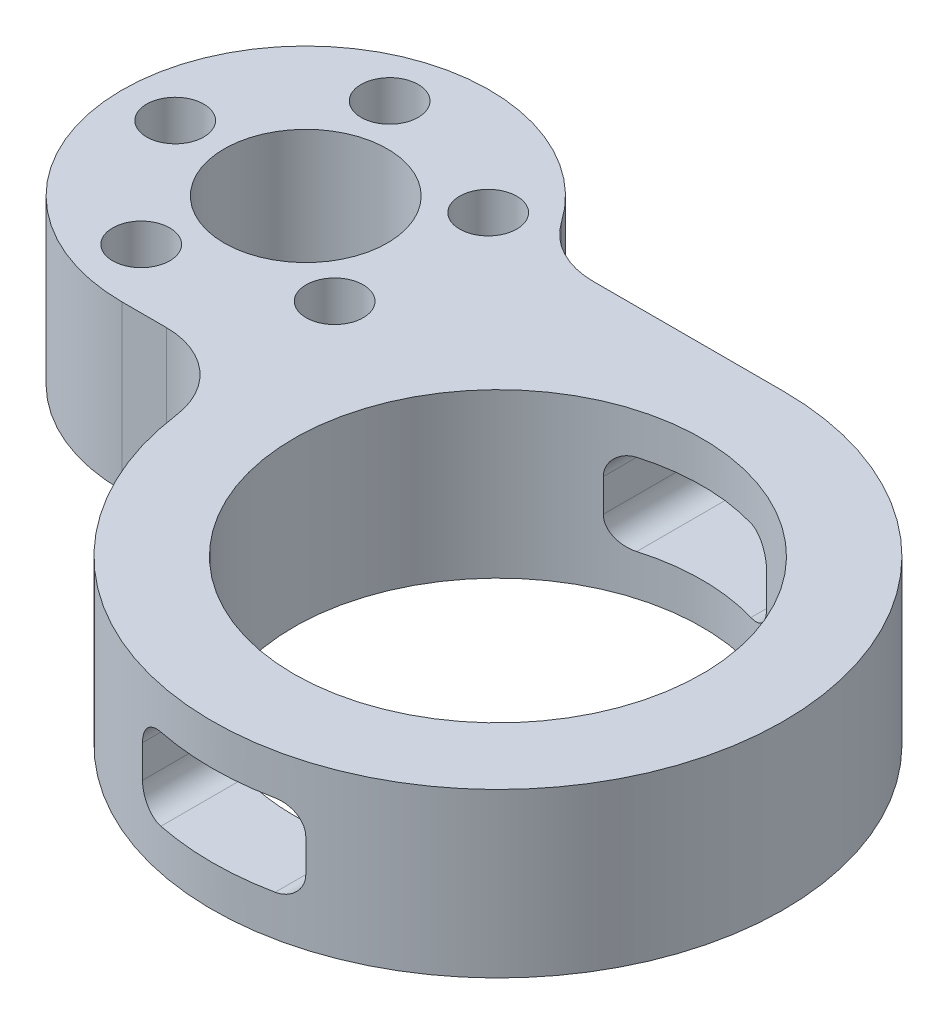
SolidWorks part; units mm, degrees
material "1060 Alloy"
ref_plane "Front Plane" through (0, 0, 0) normal (0, 0, 1) x (1, 0, 0)
ref_plane "Top Plane" through (0, 0, 0) normal (0, 1, 0) x (1, 0, 0)
ref_plane "Right Plane" through (0, 0, 0) normal (1, 0, 0) x (0, 0, -1)
sketch "Sketch1" plane through (0, 0, 0) normal (0, 1, 0) x (1, 0, 0)
  line L2 (-25, 1.9788) -> (-22.2962, 1.9788)
  line L3 (0, 17.5) -> (-11.6543, 17.5)
  circle A3 centre (0, 0) radius 12.5
  arc A4 (-17.3415, -2.3499) -> (0, 17.5) centre (0, 0) ccw
  circle A12 centre (-25, 13.2288) radius 5
  arc A13 (-15.7607, 19.6473) -> (-25, 1.9788) centre (-25, 13.2288) ccw
  arc A14 (-11.6543, 17.5) -> (-15.7607, 19.6473) centre (-11.6543, 22.5) cw
  arc A15 (-22.2962, 1.9788) -> (-17.3415, -2.3499) centre (-22.2962, -3.0212) cw
  circle A16 centre (-33, 13.2288) radius 1.75
  circle A17 centre (-27.4721, 20.8372) radius 1.75
  circle A18 centre (-18.5279, 17.931) radius 1.75
  circle A19 centre (-18.5279, 8.5265) radius 1.75
  circle A20 centre (-27.4721, 5.6203) radius 1.75
  point P14 (-40, 0)
  point P25 (-25, 13.2288)
  point P28 (-25, 13.2288)
  dimension "D2" = 17.5
  dimension "D3" = 25
  dimension "D4" = 25
  dimension "D5" = 10
  dimension "D8" = 5
  dimension "D9" = 3.5
  dimension "D10" = 8
  dimension "D6" = 22.5
  dimension "D7" = 5
  dimension "D13" = 5
  dimension "D11" = 20
  dimension "D12" = 40
extrude "Boss-Extrude1" add sketch "Sketch1" along normal blind 10
sketch "Sketch2" plane through (0, 0, 0) normal (0, 0, 1) x (1, 0, 0)
  line L1 (-3.5, 7.5) -> (3.5, 7.5)
  line L2 (-5, 6) -> (-5, 4)
  line L3 (-3.5, 2.5) -> (3.5, 2.5)
  line L4 (5, 6) -> (5, 4)
  line L5 (-5, 7.5) -> (5, 2.5) construction
  line L6 (-5, 2.5) -> (5, 7.5) construction
  arc A0 (3.5, 2.5) -> (5, 4) centre (3.5, 4) ccw
  arc A1 (-5, 4) -> (-3.5, 2.5) centre (-3.5, 4) ccw
  arc A2 (3.5, 7.5) -> (5, 6) centre (3.5, 6) cw
  arc A3 (-3.5, 7.5) -> (-5, 6) centre (-3.5, 6) ccw
  point P0 (0, 5)
  dimension "D4" = 1.5
  dimension "D1" = 5
  dimension "D2" = 10
  dimension "D3" = 5
extrude "Cut-Extrude1" cut sketch "Sketch2" against normal through all both and the other way through all
